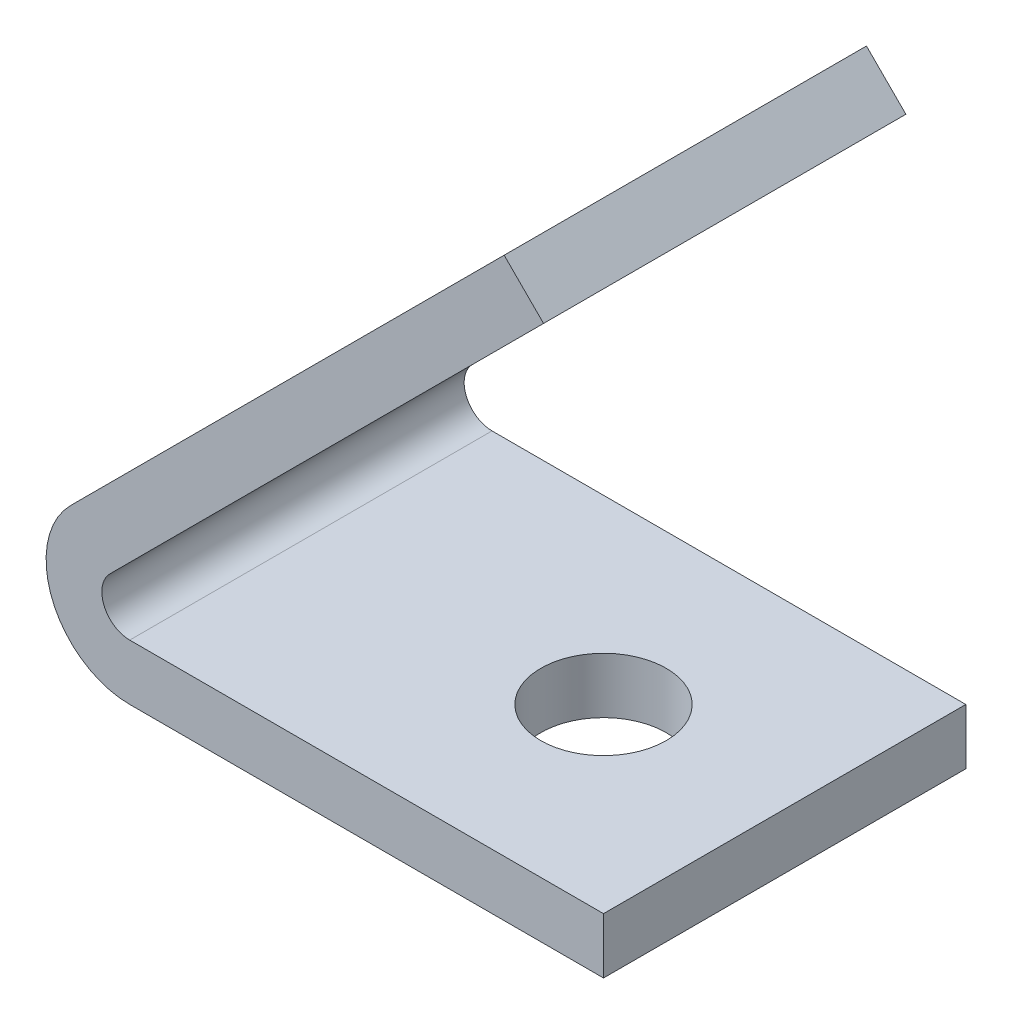
SolidWorks part; units mm, degrees
ref_plane "Front Plane" through (0, 0, 0) normal (0, 0, 1) x (1, 0, 0)
ref_plane "Top Plane" through (0, 0, 0) normal (0, 1, 0) x (1, 0, 0)
ref_plane "Right Plane" through (0, 0, 0) normal (1, 0, 0) x (0, 0, -1)
sketch "Sketch1" plane through (0, 0, 0) normal (0, 0, 1) x (1, 0, 0)
  line L0 (63.5, 0) -> (9.525, 0)
  line L1 (2.7898, 16.2602) -> (52.1812, 65.6516)
  line L2 (0, 0) -> (0, 38.0544) construction
  line L3 (0, 0) -> (9.525, 0) construction
  line L4 (-18.0859, 23.6655) -> (17.4746, -11.895) construction
  arc A0 (9.525, 0) -> (2.7898, 16.2602) centre (9.525, 9.525) cw
  point P6 (0, 0)
  dimension "D1" = 9.525
  dimension "Angle" = 45
  dimension "B" = 63.5
  dimension "A" = 79.375
extrude "Extrude-Thin1" add sketch "Sketch1" along normal mid plane 41.275 thin
sketch "Sketch2" plane through (0, 0, 0) normal (0, -1, 0) x (1, 0, 0)
  line L0 (63.5, 20.6375) -> (63.5, -20.6375) construction
  line L1 (50.0062, 0) -> (63.5, 0) construction
  circle A0 centre (42.8625, 0) radius 7.1437
  dimension "D1" = 20.6375
  dimension "Hole Size" = 14.2875
extrude "Cut-Extrude1" cut sketch "Sketch2" against normal blind 6.35
sketch "Sketch3" plane through (-6.7352, 6.7352, 0) normal (-0.7071, 0.7071, 0) x (0, 0, 1)
  line L0 (0, 83.3204) -> (0, 62.6829) construction
  line L1 (20.6375, 83.3204) -> (-20.6375, 83.3204) construction
  circle A0 centre (0, 62.6829) radius 7.1438
  dimension "D1" = 14.2875
  dimension "D2" = 20.6375
extrude "Cut-Extrude2" cut sketch "Sketch3" against normal blind 6.35
